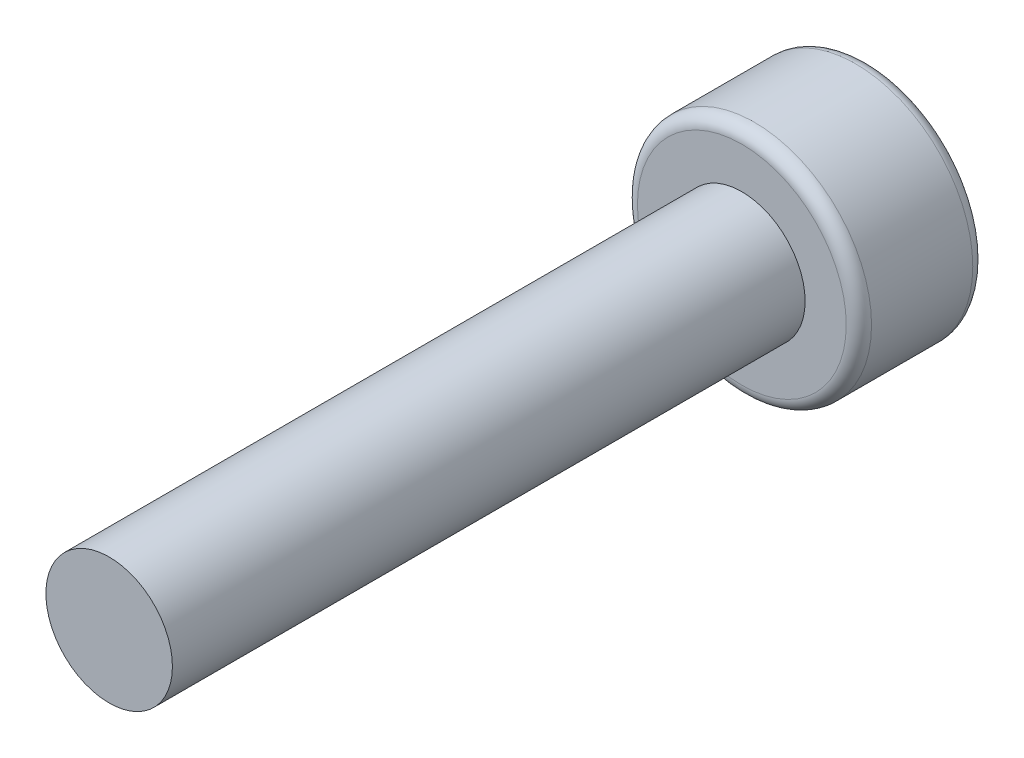
SolidWorks part; units mm, degrees
ref_plane "前视基准面" through (0, 0, 0) normal (0, 0, 1) x (1, 0, 0)
ref_plane "上视基准面" through (0, 0, 0) normal (0, 1, 0) x (1, 0, 0)
ref_plane "右视基准面" through (0, 0, 0) normal (1, 0, 0) x (0, 0, -1)
sketch "草图1" plane through (0, 0, 0) normal (0, 0, 1) x (1, 0, 0)
  circle A0 centre (0, 0) radius 1.85
  dimension "D1" = 1.85
extrude "凸台-拉伸1" add sketch "草图1" along normal blind 2
sketch "草图2" plane through (0, 0, 2) normal (0, 0, 1) x (1, 0, 0)
  circle A0 centre (0, 0) radius 1
  dimension "D1" = 1
extrude "凸台-拉伸2" add sketch "草图2" along normal blind 10
cosmetic thread "装饰螺纹线1" parameters "D2"=1
fillet "圆角1" radius 0.2 2 edges at (1.85, 0, 0) (1.85, 0, 2)
sketch "草图3" plane through (0, 0, 0) normal (0, 0, -1) x (-1, 0, 0)
  line L1 (-0.3803, 1.3571) -> (-1.3654, 0.3492)
  line L2 (-1.3654, 0.3492) -> (-0.9851, -1.0079)
  line L3 (-0.9851, -1.0079) -> (0.3803, -1.3571)
  line L4 (0.3803, -1.3571) -> (1.3654, -0.3492)
  line L5 (1.3654, -0.3492) -> (0.9851, 1.0079)
  line L6 (0.9851, 1.0079) -> (-0.3803, 1.3571)
  circle A0 centre (0, 0) radius 1.2205 construction
extrude "切除-拉伸1" cut sketch "草图3" against normal blind 1
